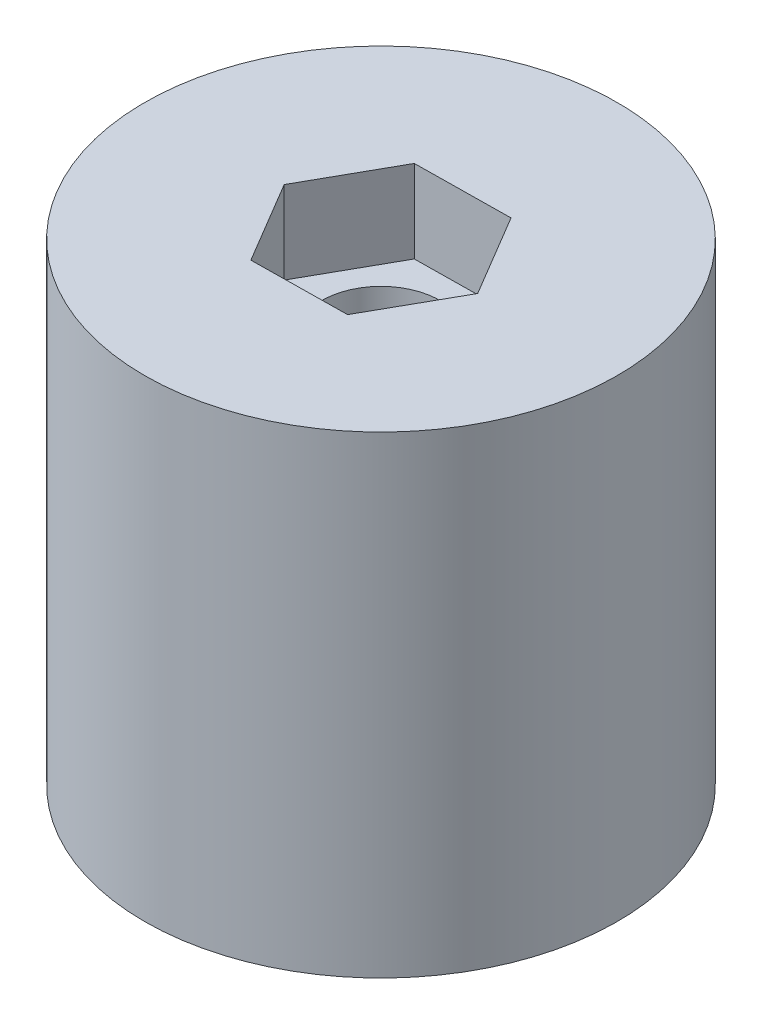
SolidWorks part; units mm, degrees
ref_plane "Front Plane" through (0, 0, 0) normal (0, 0, 1) x (1, 0, 0)
ref_plane "Top Plane" through (0, 0, 0) normal (0, 1, 0) x (1, 0, 0)
ref_plane "Right Plane" through (0, 0, 0) normal (1, 0, 0) x (0, 0, -1)
sketch "Sketch1" plane through (0, 0, 0) normal (0, 1, 0) x (1, 0, 0)
  line L0 (-55, 0) -> (55, 0) construction
  circle A0 centre (0, 0) radius 10
  circle A1 centre (0, 0) radius 2.5
  point P7 (0.089, 0)
  dimension "D1" = 5
  dimension "D2" = 20
extrude "Boss-Extrude1" add sketch "Sketch1" along normal blind 20
sketch "Sketch3" plane through (0, 20, 0) normal (0, 1, 0) x (1, 0, 0)
  line L1 (2.0643, -3.4745) -> (4.0411, 0.0505)
  line L2 (4.0411, 0.0505) -> (1.9768, 3.525)
  line L3 (1.9768, 3.525) -> (-2.0643, 3.4745)
  line L4 (-2.0643, 3.4745) -> (-4.0411, -0.0505)
  line L5 (-4.0411, -0.0505) -> (-1.9768, -3.525)
  line L6 (-1.9768, -3.525) -> (2.0643, -3.4745)
  circle A0 centre (0, 0) radius 3.5 construction
  dimension "D1" = 7
extrude "Cut-Extrude1" cut sketch "Sketch3" against normal blind 3.5
